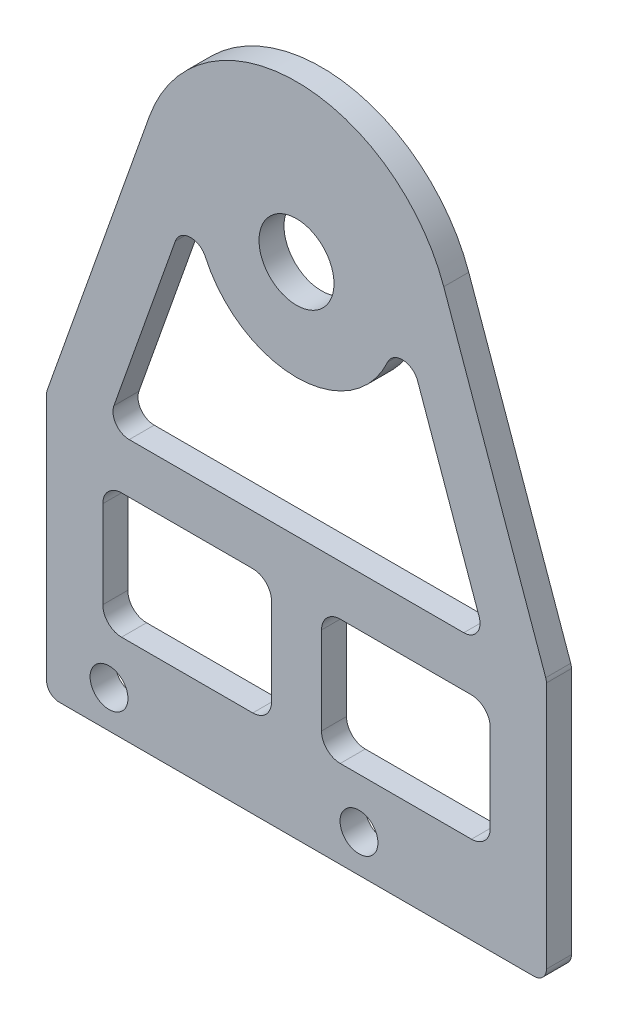
SolidWorks part; units mm, degrees
material "Thornel Mat VMA"
ref_plane "前视基准面" through (0, 0, 0) normal (0, 0, 1) x (1, 0, 0)
ref_plane "上视基准面" through (0, 0, 0) normal (0, 1, 0) x (1, 0, 0)
ref_plane "右视基准面" through (0, 0, 0) normal (1, 0, 0) x (0, 0, -1)
sketch "草图1" plane through (0, 0, 0) normal (0, 0, 1) x (1, 0, 0)
  line L0 (0, 0) -> (0, -40) construction
  line L1 (-20, -40) -> (20, -40)
  line L2 (20, -40) -> (20, -19)
  line L3 (20, -19) -> (11.7812, 4.1776)
  line L4 (-20, -19) -> (-11.7812, 4.1776)
  line L5 (-20, -40) -> (-20, -19)
  arc A0 (11.7812, 4.1776) -> (-11.7812, 4.1776) centre (0, 0) ccw
  circle A1 centre (0, 0) radius 3
  point P9 (0, -40)
  dimension "D1" = 6
  dimension "D2" = 25
  dimension "D3" = 40
  dimension "D4" = 19
  dimension "D5" = 40
extrude "凸台-拉伸1" add sketch "草图1" along normal blind 2
fillet "圆角1" radius 1 4 edges at (-20, -40, 1) (-20, -19, 1) (20, -19, 1) (20, -40, 1)
sketch "草图2" plane through (0, 0, 0) normal (0, 0, -1) x (-1, 0, 0)
  circle A0 centre (15, -37) radius 1.25 construction
  circle A1 centre (-5, -37) radius 1.25 construction
  circle A2 centre (15, -37) radius 1.25 construction
  circle A3 centre (-5, -37) radius 1.25 construction
  circle A4 centre (15, -37) radius 1.515
  circle A5 centre (-5, -37) radius 1.515
  dimension "D1" = 3.03
extrude "切除-拉伸1" cut sketch "草图2" against normal blind 10
sketch "草图3" plane through (0, 0, 0) normal (0, 0, -1) x (-1, 0, 0)
  line L0 (-7.54, 2.6737) -> (-15.2255, -19)
  line L1 (-15.2255, -19) -> (15.2255, -19)
  line L2 (15.2255, -19) -> (7.54, 2.6737)
  line L3 (11.7812, 4.1776) -> (19.9425, -18.8378) construction
  line L4 (-19.9425, -18.8378) -> (-11.7812, 4.1776) construction
  arc A0 (-7.54, 2.6737) -> (7.54, 2.6737) centre (0, 0) ccw
  dimension "D1" = 8
  dimension "D2" = 4.5
  dimension "D3" = 4.5
  dimension "D4" = 19
extrude "切除-拉伸2" cut sketch "草图3" against normal blind 10
fillet "圆角2" radius 1.3 4 edges at (-7.54, 2.6737, 1) (-15.2255, -19, 1) (15.2255, -19, 1) (7.54, 2.6737, 1)
sketch "草图4" plane through (0, 0, 0) normal (0, 0, -1) x (-1, 0, 0)
  line L0 (20, -19.1721) -> (20, -39) construction
  line L1 (-15.5, -23) -> (15.5, -23)
  line L2 (-15.5, -23) -> (-15.5, -33)
  line L3 (-15.5, -33) -> (15.5, -33)
  line L4 (15.5, -23) -> (15.5, -33)
  line L5 (-20, -39) -> (-20, -19.1721) construction
  line L6 (-13.3852, -19) -> (13.3852, -19) construction
  circle A0 centre (-5, -37) radius 1.515 construction
  dimension "D1" = 4.5
  dimension "D2" = 4.5
  dimension "D3" = 4
  dimension "D4" = 4
extrude "切除-拉伸3" cut sketch "草图4" against normal blind 10
sketch "草图5" plane through (0, 0, 0) normal (0, 0, -1) x (-1, 0, 0)
  line L0 (0, -23) -> (0, -33)
  line L1 (15.5, -23) -> (-15.5, -23) construction
  line L2 (-15.5, -33) -> (15.5, -33) construction
extrude "拉伸-薄壁1" add sketch "草图5" against normal blind 2 thin thin type mid plane wall 4
fillet "圆角4" radius 1.5 8 edges at (2, -23, 1) (2, -33, 1) (15.5, -33, 1) (-15.5, -23, 1) (-15.5, -33, 1) (-2, -33, 1) (-2, -23, 1) (15.5, -23, 1)
equation "\"D3@草图3\"=\"D2@草图3\""
